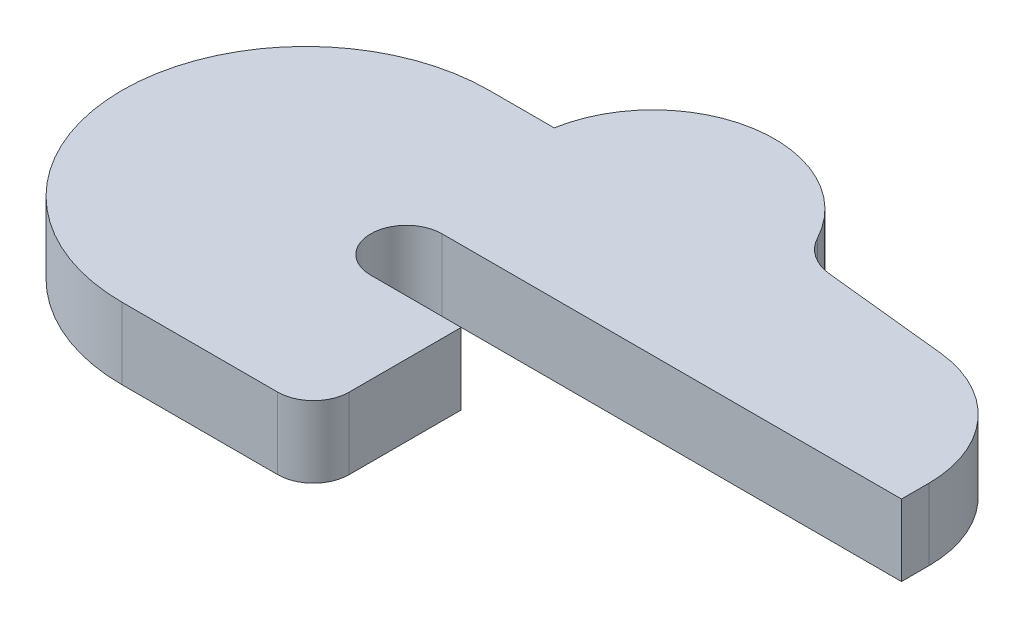
SolidWorks part; units mm, degrees
ref_plane "Front Plane" through (0, 0, 0) normal (0, 0, 1) x (1, 0, 0)
ref_plane "Top Plane" through (0, 0, 0) normal (0, 1, 0) x (1, 0, 0)
ref_plane "Right Plane" through (0, 0, 0) normal (1, 0, 0) x (0, 0, -1)
sketch "Sketch1" plane through (0, 0, 0) normal (0, 1, 0) x (1, 0, 0)
  line L0 (0, 0) -> (-3.8, 0)
  line L1 (-3.8, 3) -> (15.47, 3)
  line L2 (15.47, 3) -> (15.47, 4.149)
  line L7 (-5.3, 9.2) -> (-8.03, 9.2)
  line L9 (0, -4.7) -> (0, 0)
  line L10 (-8.03, -6.2) -> (-1.5, -6.2)
  line L11 (5.7833, 9.6692) -> (10.9926, 9.1216)
  arc A0 (-3.8, 0) -> (-3.8, 3) centre (-3.8, 1.5) cw
  arc A5 (-8.03, 9.2) -> (-8.03, -6.2) centre (-8.03, 1.5) ccw
  arc A10 (-1.5, -6.2) -> (0, -4.7) centre (-1.5, -4.7) ccw
  arc A11 (-5.3, 9.2) -> (4.2267, 10.7189) centre (-0.2759, 8.3236) cw
  arc A12 (4.2267, 10.7189) -> (5.7833, 9.6692) centre (5.9924, 11.6582) ccw
  arc A13 (15.47, 4.149) -> (10.9926, 9.1216) centre (10.47, 4.149) ccw
  point P10 (-1.0788, 13.36)
  point P15 (4.608, 9.7927)
  point P17 (4.8741, 10)
  point P19 (-15.73, 1.5)
  point P44 (-5.3, 1.5)
  dimension "10.9" = 7.7
  dimension "D4" = 1.5
  dimension "D5" = 19.56
  dimension "D6" = 6
  dimension "D7" = 2
  dimension "D10" = 31.2
  dimension "D11" = 1.5
  dimension "D2" = 5.1
  dimension "D8" = 5
  dimension "13.48" = 19.27
  dimension "80" = 90
  dimension "D9" = 3.8
  dimension "D37" = 7
extrude "Boss-Extrude2" add sketch "Sketch1" along normal blind 3
